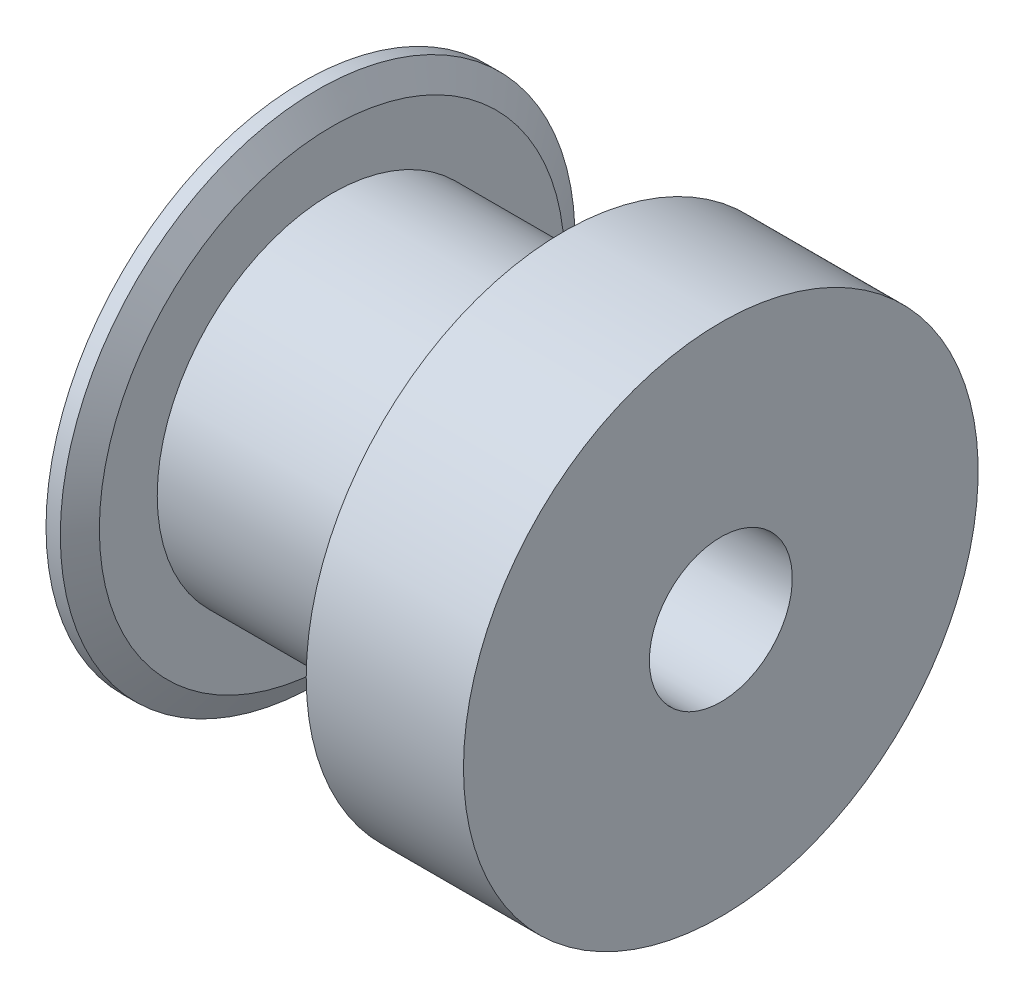
SolidWorks part; units mm, degrees
ref_plane "Piano frontale" through (0, 0, 0) normal (0, 0, 1) x (1, 0, 0)
ref_plane "Piano superiore" through (0, 0, 0) normal (0, 1, 0) x (1, 0, 0)
ref_plane "Piano destro" through (0, 0, 0) normal (1, 0, 0) x (0, 0, -1)
sketch "Schizzo1" plane through (0, 0, 0) normal (0, 0, 1) x (1, 0, 0)
  line L0 (0, 0) -> (14.6, 0) construction
  line L1 (0, 9) -> (0.5, 9)
  line L2 (0.5, 9) -> (1, 8.134)
  line L3 (1, 8.134) -> (1, 6.11)
  line L4 (1, 6.11) -> (8.6, 6.11)
  line L5 (8.6, 6.11) -> (8.6, 8.134)
  line L6 (8.6, 8.134) -> (9.1, 9)
  line L7 (9.1, 9) -> (14.6, 9)
  line L9 (14.6, 9) -> (14.6, 2.5)
  line L10 (14.6, 2.5) -> (0, 2.5)
  line L11 (0, 9) -> (0, 2.5)
  dimension "D1" = 2.5
  dimension "D2" = 9
  dimension "D3" = 6
  dimension "D4" = 7.6
  dimension "D5" = 6.11
  dimension "D6" = 1
  dimension "D7" = 9
  dimension "D8" = 150
  dimension "D9" = 0.5
revolve "Rivoluzione1" add sketch "Schizzo1" angle 360 about L0
